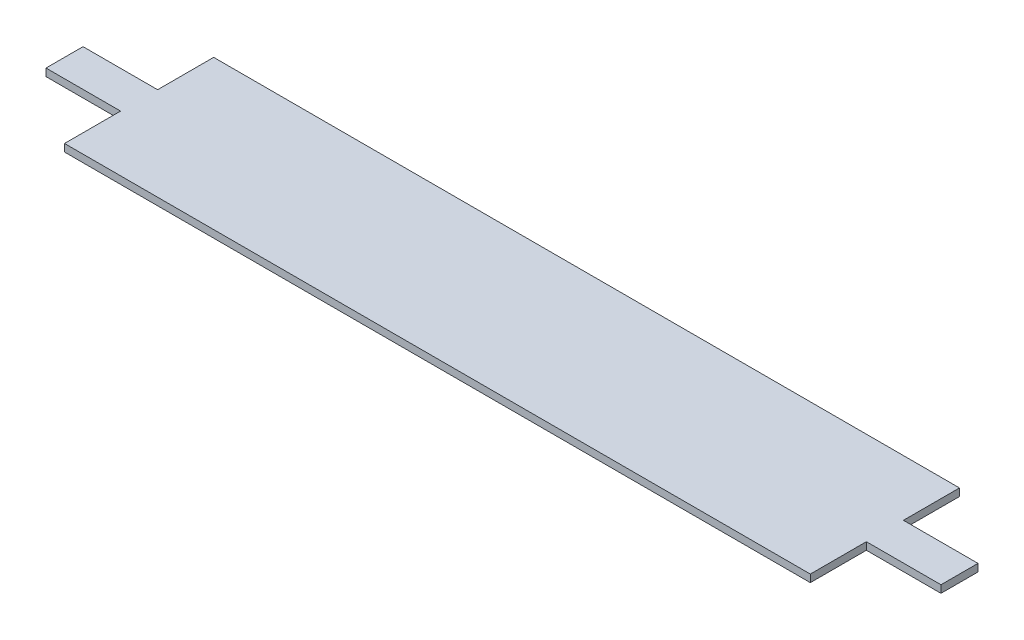
SolidWorks part; units mm, degrees
ref_plane "Front Plane" through (0, 0, 0) normal (0, 0, 1) x (1, 0, 0)
ref_plane "Top Plane" through (0, 0, 0) normal (0, 1, 0) x (1, 0, 0)
ref_plane "Right Plane" through (0, 0, 0) normal (1, 0, 0) x (0, 0, -1)
sketch "Sketch1" plane through (0, 0, 0) normal (0, 1, 0) x (1, 0, 0)
  line L0 (-25, 1.2412) -> (-25, 5)
  line L1 (25, -5) -> (-25, -5)
  line L2 (25, -5) -> (25, -1.2412)
  line L3 (25, 5) -> (-25, 5)
  line L4 (-25, -5) -> (-25, -1.2412)
  line L5 (25, 1.2412) -> (25, 5)
  line L7 (-30, -1.2412) -> (-25, -1.2412)
  line L8 (-30, -1.2412) -> (-30, 1.2412)
  line L9 (-30, 1.2412) -> (-25, 1.2412)
  line L10 (30, -1.2412) -> (30, 1.2412)
  line L16 (25, -1.2412) -> (30, -1.2412)
  line L17 (25, 1.2412) -> (30, 1.2412)
  point P0 (0, 0)
  point P6 (0, 0)
  dimension "D1" = 50
  dimension "D2" = 10
  dimension "D3" = 5
  dimension "D4" = 5
extrude "Boss-Extrude1" add sketch "Sketch1" along normal blind 0.5
